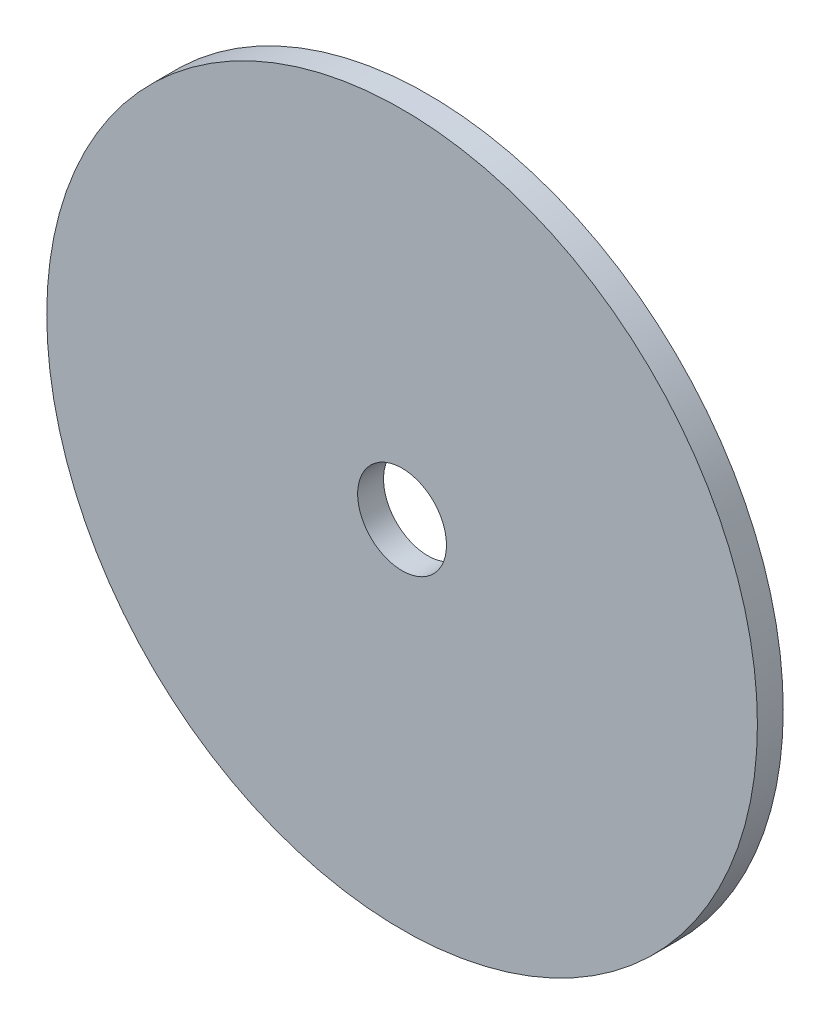
SolidWorks part; units mm, degrees
ref_plane "Plan de face" through (0, 0, 0) normal (0, 0, 1) x (1, 0, 0)
ref_plane "Plan de dessus" through (0, 0, 0) normal (0, 1, 0) x (1, 0, 0)
ref_plane "Plan de droite" through (0, 0, 0) normal (1, 0, 0) x (0, 0, -1)
sketch "Esquisse1" plane through (0, 0, 0) normal (0, 0, 1) x (1, 0, 0)
  circle A0 centre (0, 0) radius 7.5
  circle A1 centre (0, 0) radius 58
  circle A2 centre (0, 0) radius 60
  circle A3 centre (0, 0) radius 23
  circle A5 centre (0, 0) radius 25
  dimension "D1" = 120
  dimension "D2" = 116
  dimension "D3" = 15
  dimension "D4" = 50
  dimension "D5" = 46
extrude "Boss.-Extru.1" add sketch "Esquisse1" along normal blind 1.2 and the other way blind 3.1623 contours A1 A5 | A2 A1 | A5 A3 | A3 A0
